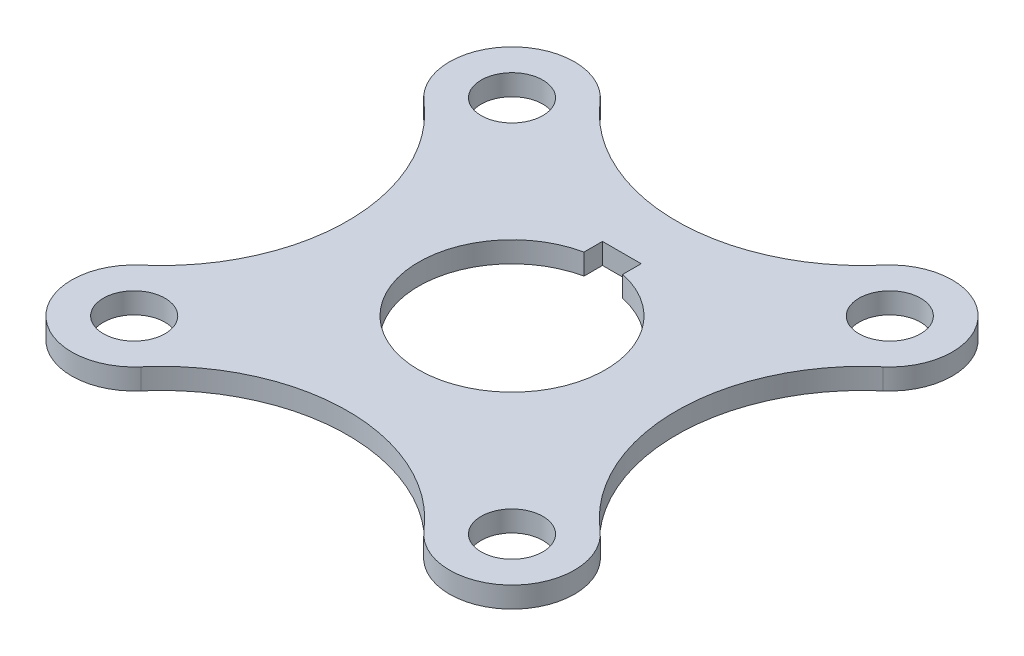
SolidWorks part; units mm, degrees
ref_plane "Front Plane" through (0, 0, 0) normal (0, 0, 1) x (1, 0, 0)
ref_plane "Top Plane" through (0, 0, 0) normal (0, 1, 0) x (1, 0, 0)
ref_plane "Right Plane" through (0, 0, 0) normal (1, 0, 0) x (0, 0, -1)
sketch "Sketch1" plane through (0, 0, 0) normal (0, 1, 0) x (1, 0, 0)
  line L0 (0, 0) -> (0, 11.3594) construction
  line L5 (0, 11.3594) -> (0, 13.3594) construction
  line L6 (2.3533, 13.3594) -> (-2.3533, 13.3594)
  line L7 (-2.3533, 13.3594) -> (-2.3533, 11.113)
  line L8 (21.1425, 21.1425) -> (22.981, 22.981) construction
  line L9 (2.3533, 13.3594) -> (2.3533, 11.113)
  circle A22 centre (0, 0) radius 32.5 construction
  circle A23 centre (22.981, 22.981) radius 2.6
  circle A24 centre (22.981, -22.981) radius 2.6
  circle A25 centre (-22.981, -22.981) radius 2.6
  arc A26 (-2.3533, 11.113) -> (2.3533, 11.113) centre (0, 0) ccw
  circle A28 centre (-22.981, 22.981) radius 2.6
  arc A29 (-17.2066, 27.9223) -> (-27.9223, 17.2066) centre (-22.981, 22.981) ccw
  arc A31 (27.9223, 17.2066) -> (17.2066, 27.9223) centre (22.981, 22.981) ccw
  arc A32 (17.2066, -27.9223) -> (27.9223, -17.2066) centre (22.981, -22.981) ccw
  arc A33 (-27.9223, -17.2066) -> (-17.2066, -27.9223) centre (-22.981, -22.981) ccw
  arc A38 (-27.9223, -17.2066) -> (-27.9223, 17.2066) centre (-42.6468, 0) ccw
  arc A39 (-17.2066, 27.9223) -> (17.2066, 27.9223) centre (0, 42.6468) ccw
  arc A40 (27.9223, 17.2066) -> (27.9223, -17.2066) centre (42.6468, 0) ccw
  arc A41 (17.2066, -27.9223) -> (-17.2066, -27.9223) centre (0, -42.6468) ccw
  circle A42 centre (22.981, -22.981) radius 7.6 construction
  circle A43 centre (-22.981, -22.981) radius 7.6 construction
  circle A44 centre (-22.981, 22.981) radius 7.6 construction
  circle A45 centre (22.981, 22.981) radius 7.6 construction
  point P0 (0, 0)
  point P2 (0, -20)
  point P8 (0, 13.3594)
  point P19 (0, 0)
  point P29 (0, 0)
  point P50 (0, 0)
  dimension "D1" = 22.7189
  dimension "D2" = 20
  dimension "D6" = 5
  dimension "D5" = 4
  dimension "D3" = 2
  dimension "D4" = 2.3533
  dimension "D8" = 4
extrude "Boss-Extrude1" add sketch "Sketch1" along normal blind 2.54
sketch "Sketch2" plane through (0, 2.54, 0) normal (0, 1, 0) x (1, 0, 0)
  circle A0 centre (-22.981, 22.981) radius 3.75
  circle A1 centre (22.981, 22.981) radius 3.75
  circle A2 centre (22.981, -22.981) radius 3.75
  circle A3 centre (-22.981, -22.981) radius 3.75
  circle A4 centre (22.981, -22.981) radius 2.6 construction
  circle A5 centre (-22.981, -22.981) radius 2.6 construction
  circle A6 centre (22.981, 22.981) radius 2.6 construction
  circle A7 centre (-22.981, 22.981) radius 2.6 construction
  arc A8 (-27.9223, -17.2066) -> (-27.9223, 17.2066) centre (-42.6468, 0) ccw
  arc A9 (-27.9223, -17.2066) -> (-17.2066, -27.9223) centre (-22.981, -22.981) ccw
  arc A10 (17.2066, -27.9223) -> (-17.2066, -27.9223) centre (0, -42.6468) ccw
  arc A11 (17.2066, -27.9223) -> (27.9223, -17.2066) centre (22.981, -22.981) ccw
  arc A12 (27.9223, 17.2066) -> (27.9223, -17.2066) centre (42.6468, 0) ccw
  arc A13 (27.9223, 17.2066) -> (17.2066, 27.9223) centre (22.981, 22.981) ccw
  arc A14 (-17.2066, 27.9223) -> (17.2066, 27.9223) centre (0, 42.6468) ccw
  arc A15 (-17.2066, 27.9223) -> (-27.9223, 17.2066) centre (-22.981, 22.981) ccw
  arc A16 (-27.9223, -17.2066) -> (-27.9223, 17.2066) centre (-42.6468, 0) ccw
  arc A17 (-27.9223, -17.2066) -> (-17.2066, -27.9223) centre (-22.981, -22.981) ccw
  arc A18 (17.2066, -27.9223) -> (-17.2066, -27.9223) centre (0, -42.6468) ccw
  arc A19 (17.2066, -27.9223) -> (27.9223, -17.2066) centre (22.981, -22.981) ccw
  arc A20 (27.9223, 17.2066) -> (27.9223, -17.2066) centre (42.6468, 0) ccw
  arc A21 (27.9223, 17.2066) -> (17.2066, 27.9223) centre (22.981, 22.981) ccw
  arc A22 (-17.2066, 27.9223) -> (17.2066, 27.9223) centre (0, 42.6468) ccw
  arc A23 (-17.2066, 27.9223) -> (-27.9223, 17.2066) centre (-22.981, 22.981) ccw
  circle A24 centre (22.981, -22.981) radius 2.6
  circle A25 centre (-22.981, -22.981) radius 2.6
  circle A26 centre (22.981, 22.981) radius 2.6
  circle A27 centre (-22.981, 22.981) radius 2.6
  point P26 (0, 0)
  circle M11 centre (-22.981, -22.981) radius 2.6
  circle M12 centre (22.981, 22.981) radius 2.6
  circle M25 centre (22.981, -22.981) radius 2.6
  circle M26 centre (-22.981, 22.981) radius 2.6
  dimension "D2" = 4
  dimension "D3" = 7.5
  dimension "D1" = 0
extrude "Cut-Extrude1" cut sketch "Sketch2" against normal through all contours A0 M26 | A1 M12 | A2 M25 | A3 M11
